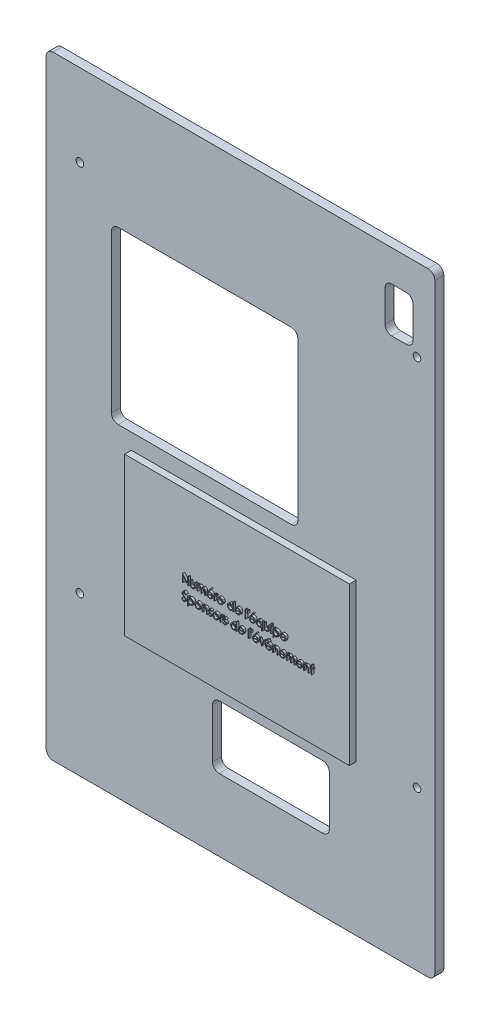
SolidWorks part; units mm, degrees
material "Verre"
ref_plane "Plan de face" through (0, 0, 0) normal (0, 0, 1) x (1, 0, 0)
ref_plane "Plan de dessus" through (0, 0, 0) normal (0, 1, 0) x (1, 0, 0)
ref_plane "Plan de droite" through (0, 0, 0) normal (1, 0, 0) x (0, 0, -1)
sketch "Esquisse1" plane through (0, 0, 0) normal (0, 0, 1) x (1, 0, 0)
  line L1 (0, 0) -> (172.93, 0)
  line L2 (0, 0) -> (0, 273)
  line L3 (0, 273) -> (172.93, 273)
  line L4 (172.93, 0) -> (172.93, 273)
  line L5 (74, 60) -> (126, 60)
  line L6 (74, 60) -> (74, 32)
  line L7 (74, 32) -> (126, 32)
  line L8 (126, 60) -> (126, 32)
  line L9 (29, 220) -> (112, 220)
  line L10 (29, 220) -> (29, 144)
  line L11 (29, 144) -> (112, 144)
  line L12 (112, 220) -> (112, 144)
  line L13 (163.25, 259) -> (150.75, 259)
  line L14 (163.25, 259) -> (163.25, 239)
  line L15 (163.25, 239) -> (150.75, 239)
  line L16 (150.75, 259) -> (150.75, 239)
  line L17 (163.25, 259) -> (150.75, 239) construction
  line L18 (163.25, 239) -> (150.75, 259) construction
  circle A0 centre (15, 236.5) radius 1.5
  circle A1 centre (165, 236.5) radius 1.5
  circle A2 centre (15, 70.5) radius 1.5
  circle A3 centre (165, 70.5) radius 1.5
  point P21 (157, 249)
  dimension "D5" = 3
  dimension "D8" = 3
  dimension "D11" = 3
  dimension "D22" = 3
  dimension "D25" = 12.5
  dimension "D1" = 172.93
  dimension "D2" = 273
  dimension "D3" = 36.5
  dimension "D4" = 15
  dimension "D6" = 7.93
  dimension "D7" = 36.5
  dimension "D9" = 70.5
  dimension "D10" = 15
  dimension "D12" = 74
  dimension "D13" = 52
  dimension "D14" = 28
  dimension "D15" = 32
  dimension "D16" = 29
  dimension "D17" = 83
  dimension "D18" = 144
  dimension "D19" = 76
  dimension "D20" = 7.93
  dimension "D21" = 70.5
  dimension "D23" = 15.93
  dimension "D24" = 24
  dimension "D26" = 20
extrude "Boss.-Extru.1" add sketch "Esquisse1" along normal blind 4
hole_wizard "Dégagement M31" positions "Esquisse2" profile "Esquisse3" hole size "M3" standard "ISO" end condition through all
sketch "Esquisse2" plane through (0, 0, 4) normal (0, 0, 1) x (1, 0, 0)
  point P0 (15, 236.5)
  point P3 (15, 70.5)
  point P6 (165, 236.5)
  point P9 (165, 70.5)
sketch "Esquisse3" plane through (15, 236.5, 4) normal (1, 0, 0) x (0, -1, 0)
  line L0 (0, 0) -> (0, 4)
  line L1 (0, 4) -> (1.7, 4)
  line L2 (1.7, 4) -> (1.7, 0)
  line L5 (1.7, 0) -> (0, 0)
  line L11 (0, -6.35) -> (0, 107.95) construction
  dimension "Diamètre du perçage jusqu'au prochain" = 3.4
  dimension "Profondeur du perçage jusqu'au prochain" = 4
fillet "Congé1" radius 3 16 edges at (0, 0, 2) (172.93, 0, 2) (126, 32, 2) (74, 32, 2) (126, 60, 2) (74, 60, 2) (112, 144, 2) (29, 144, 2) (112, 220, 2) (29, 220, 2) (172.93, 273, 2) (0, 273, 2) (163.25, 239, 2) (163.25, 259, 2) (150.75, 259, 2) (150.75, 239, 2)
sketch "Esquisse5" plane through (0, 0, 4) normal (0, 0, 1) x (1, 0, 0)
  line L0 (32, 144) -> (109, 144) construction
  line L1 (37.93, 137) -> (137.93, 137)
  line L2 (37.93, 137) -> (37.93, 67)
  line L3 (37.93, 67) -> (137.93, 67)
  line L4 (137.93, 137) -> (137.93, 67)
  line L5 (172.93, 3) -> (172.93, 270) construction
  line L6 (37.93, 102) -> (137.93, 102) construction
  dimension "D1" = 100
  dimension "D2" = 70
  dimension "D3" = 7
  dimension "D4" = 35
extrude "Boss.-Extru.3" add sketch "Esquisse5" along normal blind 3 contours L2 L3 L4 L1
sketch "Esquisse6" plane through (0, 0, 7) normal (0, 0, 1) x (1, 0, 0)
  text T0 "Numéro de l'équipe\r\nSponsors de l'évènement"
extrude "Boss.-Extru.4" add sketch "Esquisse6" along normal blind 1
